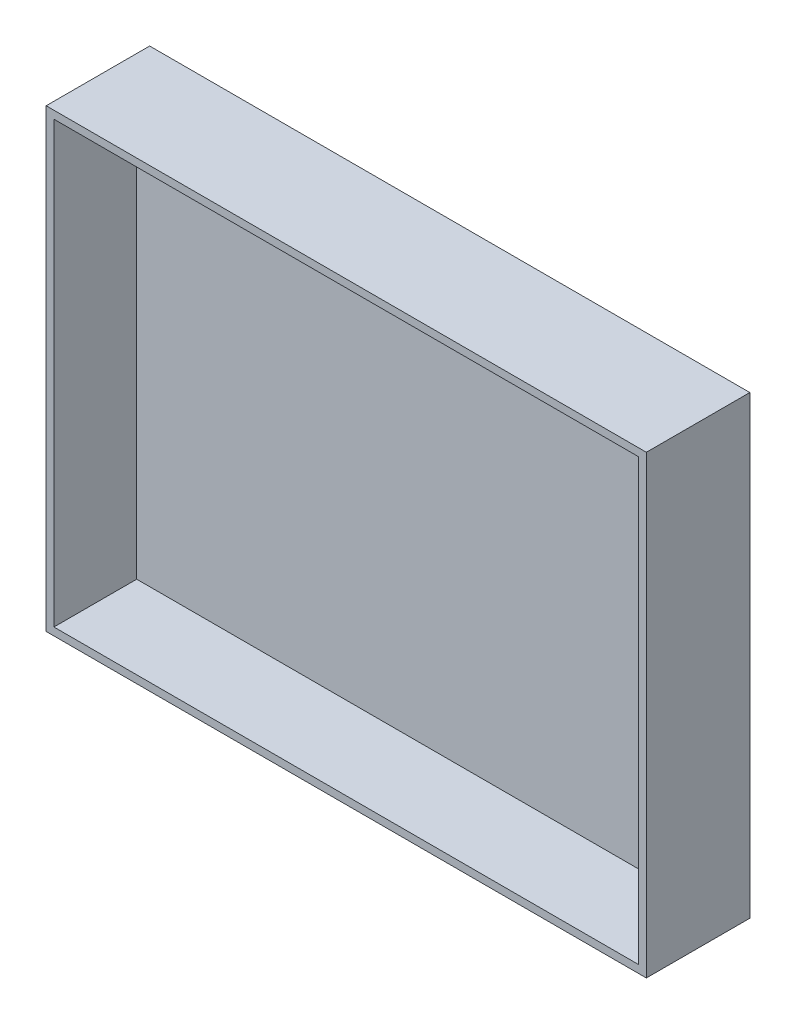
SolidWorks part; units mm, degrees
ref_plane "Front Plane" through (0, 0, 0) normal (0, 0, 1) x (1, 0, 0)
ref_plane "Top Plane" through (0, 0, 0) normal (0, 1, 0) x (1, 0, 0)
ref_plane "Right Plane" through (0, 0, 0) normal (1, 0, 0) x (0, 0, -1)
sketch "Sketch1" plane through (0, 0, 0) normal (0, 0, 1) x (1, 0, 0)
  line L1 (-28.25, -21.25) -> (28.25, -21.25)
  line L2 (-28.25, -21.25) -> (-28.25, 21.25)
  line L3 (-28.25, 21.25) -> (28.25, 21.25)
  line L4 (28.25, -21.25) -> (28.25, 21.25)
  line L5 (-28.25, -21.25) -> (28.25, 21.25) construction
  line L6 (-28.25, 21.25) -> (28.25, -21.25) construction
  line L7 (29, -22) -> (-29, -22)
  line L8 (29, -22) -> (29, 22)
  line L9 (29, 22) -> (-29, 22)
  line L10 (-29, -22) -> (-29, 22)
  line L11 (29, -22) -> (-29, 22) construction
  line L12 (29, 22) -> (-29, -22) construction
  point P0 (0, 0)
  point P6 (0, 0)
  dimension "D1" = 56.5
  dimension "D2" = 42.5
  dimension "D3" = 44
  dimension "D4" = 58
extrude "Boss-Extrude1" add sketch "Sketch1" along normal blind 10
sketch "Sketch2" plane through (0, 0, 0) normal (0, 0, 1) x (1, 0, 0)
  line L1 (-29, -22) -> (29, -22)
  line L2 (-29, -22) -> (-29, 22)
  line L3 (-29, 22) -> (29, 22)
  line L4 (29, -22) -> (29, 22)
  line L5 (-29, -22) -> (29, 22) construction
  line L6 (-29, 22) -> (29, -22) construction
  point P0 (0, 0)
extrude "Boss-Extrude2" add sketch "Sketch2" along normal blind 2
